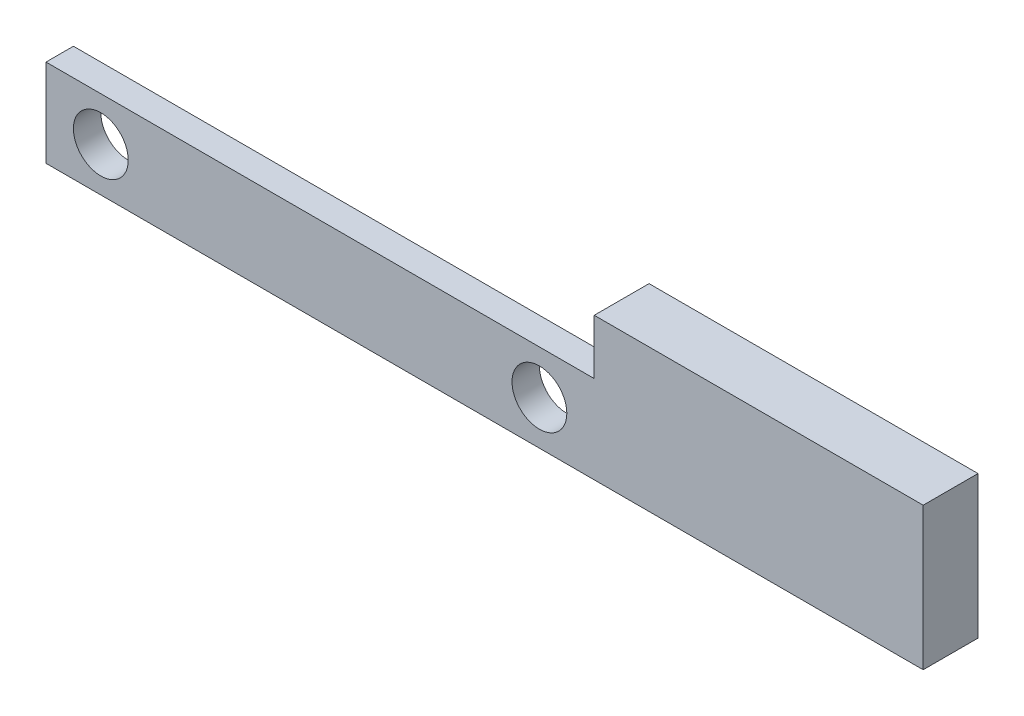
SolidWorks part; units mm, degrees
ref_plane "Plan de face" through (0, 0, 0) normal (0, 0, 1) x (1, 0, 0)
ref_plane "Plan de dessus" through (0, 0, 0) normal (0, 1, 0) x (1, 0, 0)
ref_plane "Plan de droite" through (0, 0, 0) normal (1, 0, 0) x (0, 0, -1)
sketch "Esquisse2" plane through (0, 0, 0) normal (0, 0, 1) x (1, 0, 0)
  line L0 (0, 0) -> (0, 8)
  line L1 (0, 8) -> (50, 8)
  line L2 (50, 8) -> (50, 13)
  line L3 (50, 13) -> (80, 13)
  line L4 (80, 13) -> (80, 0)
  line L5 (80, 0) -> (0, 0)
  dimension "D1" = 8
  dimension "D2" = 5
  dimension "D3" = 50
  dimension "D4" = 30
extrude "Boss.-Extru.1" add sketch "Esquisse2" along normal blind 5
sketch "Esquisse3" plane through (0, 0, 5) normal (0, 0, 1) x (1, 0, 0)
  line L0 (0, 4) -> (80, 4) construction
  line L1 (0, 8) -> (0, 0) construction
  line L2 (80, 0) -> (80, 13) construction
  circle A0 centre (5, 4) radius 2.5
  circle A1 centre (45, 4) radius 2.5
  dimension "D1" = 5
  dimension "D2" = 5
  dimension "D3" = 5
  dimension "D4" = 40
extrude "Enlèv. mat.-Extru.1" cut sketch "Esquisse3" against normal blind 5
sketch "Esquisse5" plane through (0, 0, 0) normal (0, 0, -1) x (-1, 0, 0)
  line L1 (0, 0) -> (-50, 0)
  line L2 (0, 0) -> (0, 8)
  line L3 (0, 8) -> (-50, 8)
  line L4 (-50, 0) -> (-50, 8)
extrude "Enlèv. mat.-Extru.3" cut sketch "Esquisse5" against normal blind 2.5
